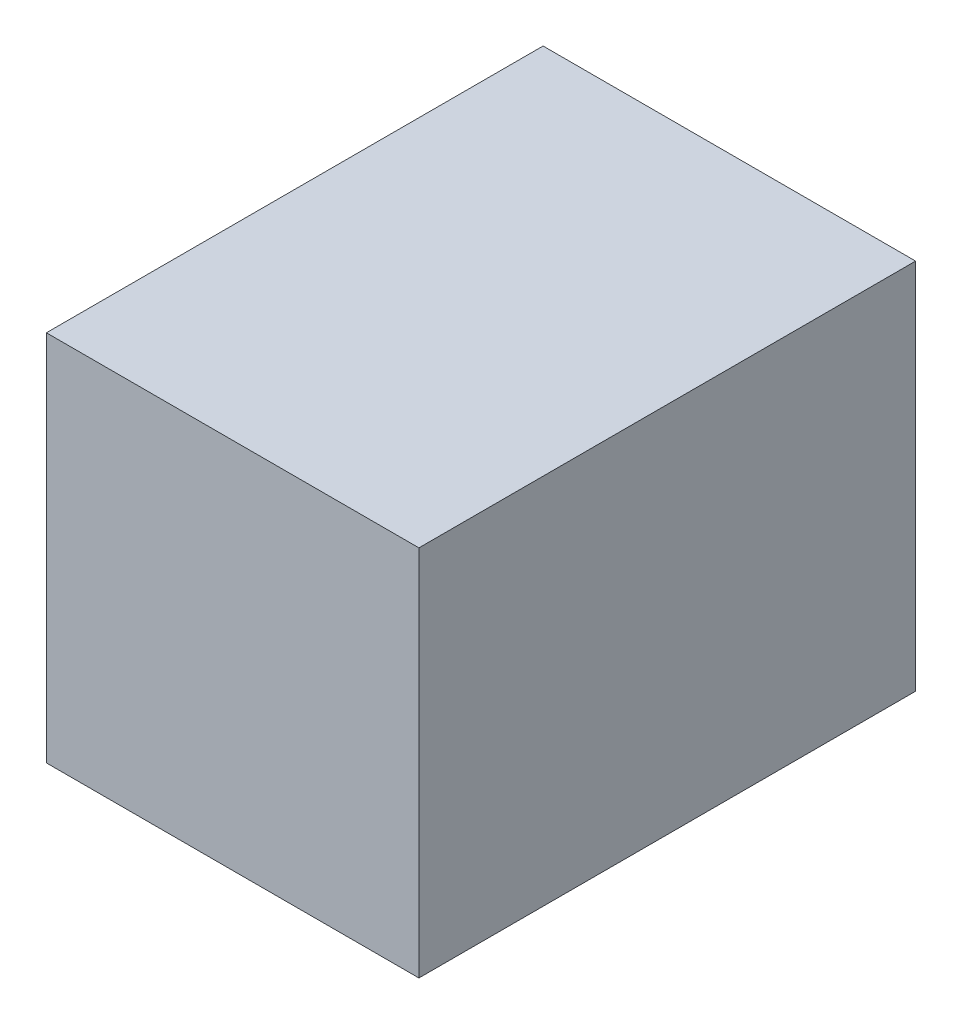
SolidWorks part; units mm, degrees
ref_plane "Front Plane" through (0, 0, 0) normal (0, 0, 1) x (1, 0, 0)
ref_plane "Top Plane" through (0, 0, 0) normal (0, 1, 0) x (1, 0, 0)
ref_plane "Right Plane" through (0, 0, 0) normal (1, 0, 0) x (0, 0, -1)
sketch "Sketch1" plane through (0, 0, 0) normal (0, 1, 0) x (1, 0, 0)
  line L1 (-750, -1000) -> (750, -1000)
  line L2 (-750, -1000) -> (-750, 1000)
  line L3 (-750, 1000) -> (750, 1000)
  line L4 (750, -1000) -> (750, 1000)
  line L5 (-750, -1000) -> (750, 1000) construction
  line L6 (-750, 1000) -> (750, -1000) construction
  point P0 (0, 0)
  dimension "D1" = 1500
  dimension "D2" = 2000
extrude "Boss-Extrude1" add sketch "Sketch1" along normal blind 1500
